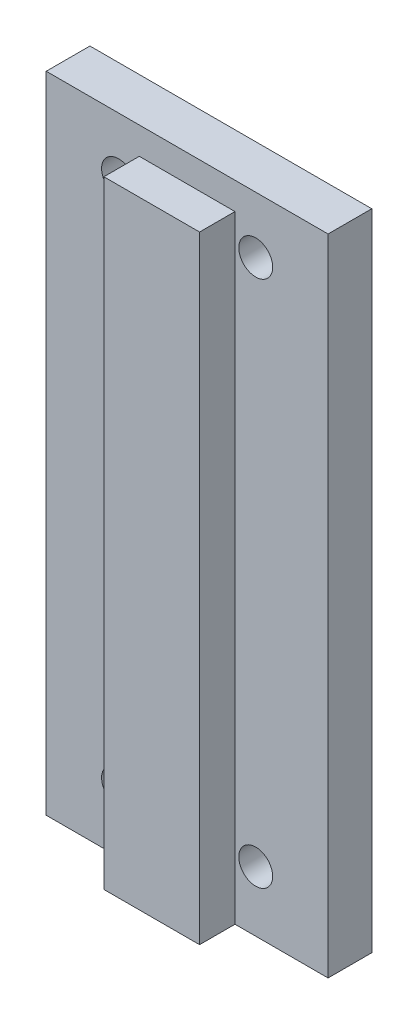
SolidWorks part; units mm, degrees
ref_plane "Front Plane" through (0, 0, 0) normal (0, 0, 1) x (1, 0, 0)
ref_plane "Top Plane" through (0, 0, 0) normal (0, 1, 0) x (1, 0, 0)
ref_plane "Right Plane" through (0, 0, 0) normal (1, 0, 0) x (0, 0, -1)
sketch "Sketch2" plane through (0, 0, 0) normal (0, 0, 1) x (1, 0, 0)
  line L1 (0, 0) -> (37.4, 0)
  line L2 (0, 0) -> (0, 85.5)
  line L3 (0, 85.5) -> (37.4, 85.5)
  line L4 (37.4, 0) -> (37.4, 85.5)
  dimension "D1" = 85.5
  dimension "37,4" = 37.4
extrude "Boss-Extrude1" add sketch "Sketch2" along normal blind 5.8
sketch "Sketch3" plane through (0, 0, 5.8) normal (0, 0, 1) x (1, 0, 0)
  line L0 (0, 0) -> (37.4, 0) construction
  line L1 (12.35, 0) -> (25.05, 0)
  line L2 (12.35, 0) -> (12.35, 81.9)
  line L3 (12.35, 81.9) -> (25.05, 81.9)
  line L4 (25.05, 0) -> (25.05, 81.9)
  line L5 (37.4, 0) -> (37.4, 85.5) construction
  line L7 (37.4, 85.5) -> (0, 85.5) construction
  dimension "D1" = 12.7
  dimension "D2" = 12.35
  dimension "D3" = 3.6
extrude "Boss-Extrude2" add sketch "Sketch3" along normal blind 4.7
sketch "Sketch4" plane through (0, 0, 0) normal (0, 0, -1) x (-1, 0, 0)
  line L1 (-37.4, 0) -> (-37.4, 85.5) construction
  line L2 (0, 85.5) -> (0, 0) construction
  line L3 (-37.4, 85.5) -> (0, 85.5) construction
  circle A0 centre (-27.8, 78) radius 2.25
  circle A1 centre (-9.6, 78) radius 2.25
  circle A2 centre (-9.6, 8) radius 2.25
  circle A3 centre (-27.8, 8) radius 2.25
  dimension "D1" = 4.5
  dimension "D2" = 4.5
  dimension "D3" = 4.5
  dimension "D4" = 4.5
  dimension "D5" = 18.2
  dimension "D6" = 9.6
  dimension "D7" = 9.6
  dimension "D8" = 9.6
  dimension "D9" = 9.6
  dimension "D11" = 70
  dimension "18,2" = 18.2
  dimension "D10" = 7.5
extrude "Cut-Extrude1" cut sketch "Sketch4" against normal up to surface (5.8 mm away) up to face at (18.7, 41.85, 5.8)
